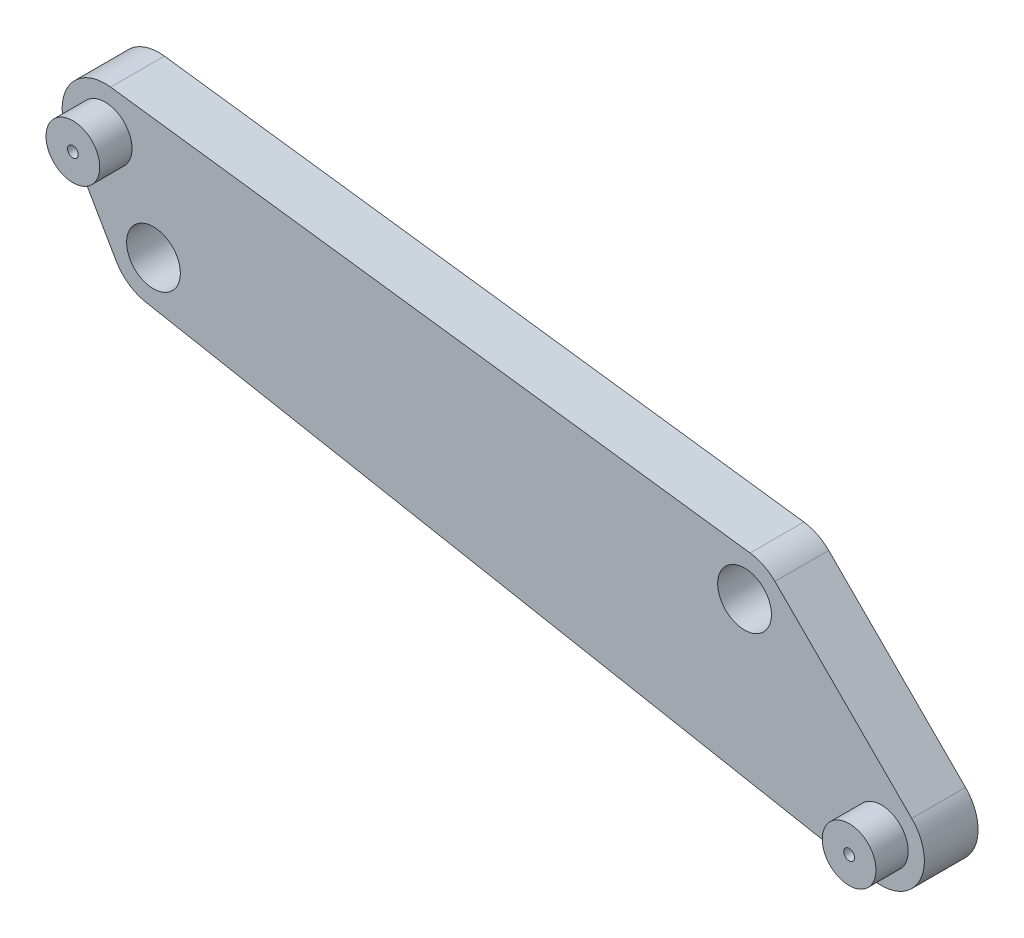
SolidWorks part; units mm, degrees
material "ABS"
ref_plane "Front Plane" through (0, 0, 0) normal (0, 0, 1) x (1, 0, 0)
ref_plane "Top Plane" through (0, 0, 0) normal (0, 1, 0) x (1, 0, 0)
ref_plane "Right Plane" through (0, 0, 0) normal (1, 0, 0) x (0, 0, -1)
sketch "Sketch1" plane through (0, 0, 0) normal (0, 0, 1) x (1, 0, 0)
  line L0 (0, 0) -> (-55, 0)
  line L1 (-55, 0) -> (-59.5, 7.7942)
  line L2 (0, 0) -> (12.7279, -12.7279)
  dimension "D1" = 55
  dimension "D2" = 9
  dimension "D3" = 18
  dimension "D4" = 120
  dimension "D5" = 135
sketch "Sketch2" plane through (0, 0, 0) normal (0, 0, 1) x (1, 0, 0)
  line L0 (-58.9805, 11.7603) -> (0.5195, 3.9661)
  line L1 (2.8284, 2.8284) -> (15.5563, -9.8995)
  line L2 (11.9891, -16.6591) -> (-55.7388, -3.9312)
  line L3 (-58.4641, -2) -> (-62.9641, 5.7942)
  circle A0 centre (-55, 0) radius 2.5
  circle A1 centre (-59.5, 7.7942) radius 2.5
  arc A2 (-58.9805, 11.7603) -> (-62.9641, 5.7942) centre (-59.5, 7.7942) ccw
  arc A3 (-58.4641, -2) -> (-55.7388, -3.9312) centre (-55, 0) ccw
  circle A4 centre (0, 0) radius 2.5
  circle A5 centre (12.7279, -12.7279) radius 2.5
  arc A6 (2.8284, 2.8284) -> (0.5195, 3.9661) centre (0, 0) ccw
  arc A7 (11.9891, -16.6591) -> (15.5563, -9.8995) centre (12.7279, -12.7279) ccw
  dimension "D1" = 5
  dimension "D2" = 5
  dimension "D3" = 5
  dimension "D4" = 5
  dimension "D5" = 8
  dimension "D6" = 8
  dimension "D7" = 8
  dimension "D8" = 8
extrude "Boss-Extrude1" add sketch "Sketch2" along normal blind 5
sketch "Sketch4" plane through (0, 0, 0) normal (0, 0, -1) x (-1, 0, 0)
  circle A0 centre (59.5, 7.7942) radius 2.5
  circle A1 centre (59.5, 7.7942) radius 0.5
  circle A2 centre (-12.7279, -12.7279) radius 2.5
  circle A3 centre (-12.7279, -12.7279) radius 0.5
  dimension "D1" = 1
  dimension "D2" = 5
  dimension "D3" = 5
  dimension "D4" = 1
extrude "Boss-Extrude3" add sketch "Sketch4" against normal blind 8
